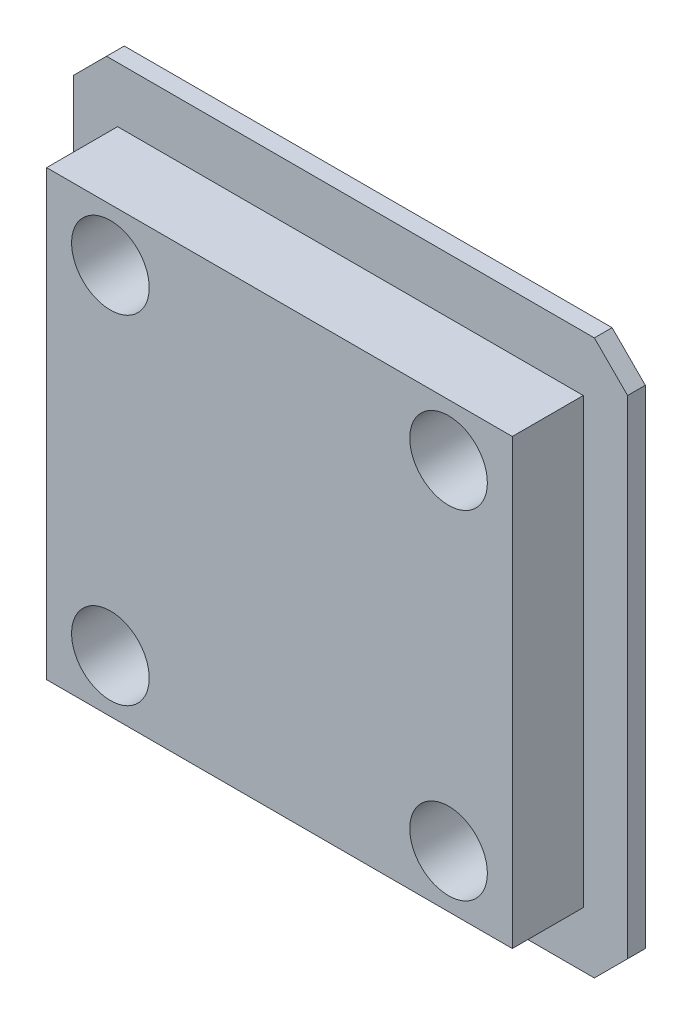
SolidWorks part; units mm, degrees
ref_plane "前视基准面" through (0, 0, 0) normal (0, 0, 1) x (1, 0, 0)
ref_plane "上视基准面" through (0, 0, 0) normal (0, 1, 0) x (1, 0, 0)
ref_plane "右视基准面" through (0, 0, 0) normal (1, 0, 0) x (0, 0, -1)
other "Configuration Table"
sketch "草图1" plane through (0, 0, 0) normal (0, 0, 1) x (1, 0, 0)
  line L0 (-22, -25) -> (22, -25)
  line L1 (22, -25) -> (25, -22)
  line L2 (25, -22) -> (25, 22)
  line L3 (25, 22) -> (22, 25)
  line L4 (22, 25) -> (-22, 25)
  line L5 (-22, 25) -> (-25, 22)
  line L6 (-25, 22) -> (-25, -22)
  line L7 (-25, -22) -> (-22, -25)
  circle A0 centre (-15.25, -15.25) radius 1.65
  circle A1 centre (-15.25, 15.25) radius 1.65
  circle A2 centre (15.25, -15.25) radius 1.65
  circle A3 centre (15.25, 15.25) radius 1.65
extrude "飞控电调一体板占位" add sketch "草图1" along normal blind 1.6
sketch "草图2" plane through (0, 0, 0) normal (0, 0, 1) x (1, 0, 0)
  line L0 (-21, -20) -> (21, -20)
  line L1 (21, -20) -> (21, 20)
  line L2 (21, 20) -> (-21, 20)
  line L3 (-21, 20) -> (-21, -20)
extrude "元件及接口高度包络" add sketch "草图2" along normal blind 6.4 from offset 1.6
sketch "草图3" plane through (0, 0, 0) normal (0, 0, 1) x (1, 0, 0)
  circle A0 centre (-15.25, -15.25) radius 3.5
  circle A1 centre (-15.25, 15.25) radius 3.5
  circle A2 centre (15.25, -15.25) radius 3.5
  circle A3 centre (15.25, 15.25) radius 3.5
extrude "安装螺钉头元件避让包络" cut sketch "草图3" along normal blind 6.4 from offset 1.6
